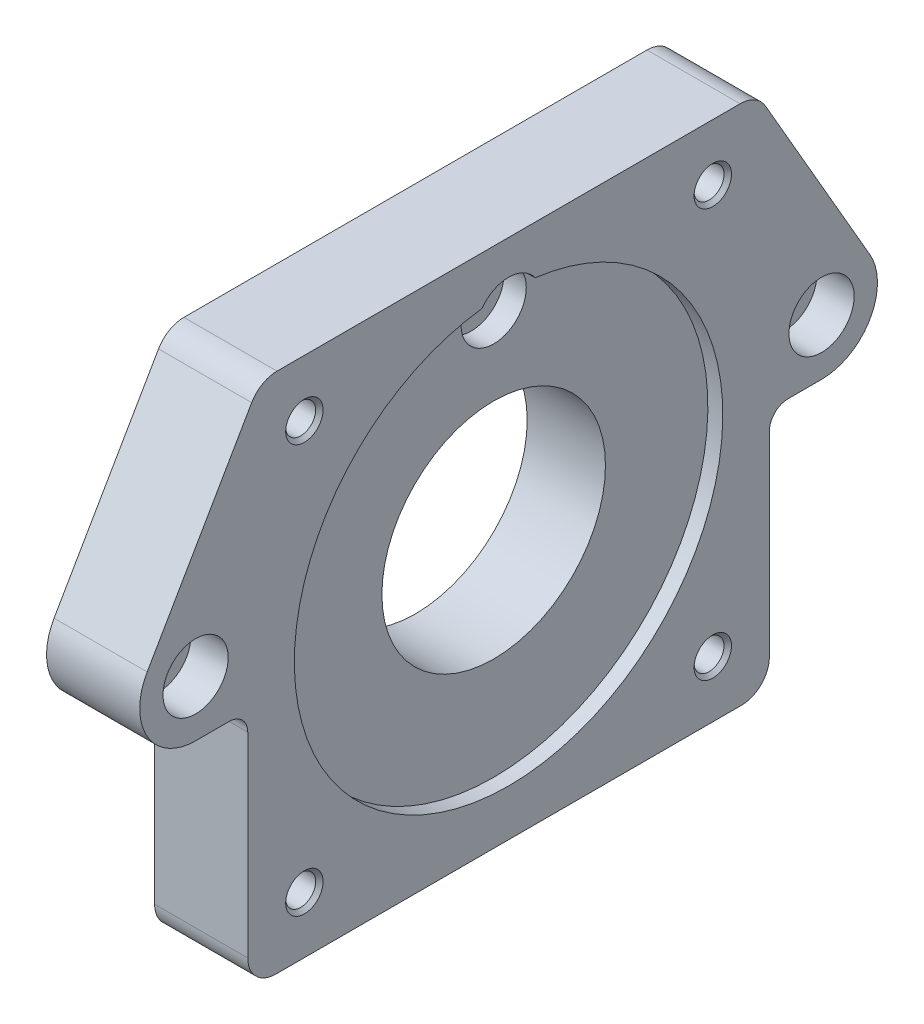
SolidWorks part; units mm, degrees
ref_plane "Front Plane" through (0, 0, 0) normal (0, 0, 1) x (1, 0, 0)
ref_plane "Top Plane" through (0, 0, 0) normal (0, 1, 0) x (1, 0, 0)
ref_plane "Right Plane" through (0, 0, 0) normal (1, 0, 0) x (0, 0, -1)
sketch "Sketch1" plane through (0, 0, 0) normal (1, 0, 0) x (0, 0, -1)
  line L0 (-39.4612, 44.45) -> (39.4612, 44.45)
  line L1 (-43.7816, 41.9556) -> (-61.5889, 11.1125)
  line L2 (43.7816, 41.9556) -> (61.5889, 11.1125)
  line L3 (53.34, -3.175) -> (44.45, -3.175)
  line L4 (-44.45, -3.175) -> (-44.45, -44.45)
  line L5 (-44.45, -44.45) -> (44.45, -44.45)
  line L6 (-53.34, -3.175) -> (-44.45, -3.175)
  line L7 (44.45, -44.45) -> (44.45, -3.175)
  line L9 (-34.798, 34.798) -> (34.798, 34.798) construction
  line L10 (-34.798, 34.798) -> (-34.798, -34.798) construction
  line L11 (-34.798, -34.798) -> (34.798, -34.798) construction
  line L12 (34.798, 34.798) -> (34.798, -34.798) construction
  line L13 (-34.798, 34.798) -> (34.798, -34.798) construction
  line L14 (-34.798, -34.798) -> (34.798, 34.798) construction
  circle A0 centre (0, 0) radius 19.05
  arc A1 (61.5889, 11.1125) -> (53.34, -3.175) centre (53.34, 6.35) cw
  arc A2 (39.4612, 44.45) -> (43.7816, 41.9556) centre (39.4612, 39.4612) cw
  arc A3 (-39.4612, 44.45) -> (-43.7816, 41.9556) centre (-39.4612, 39.4612) ccw
  arc A4 (-53.34, -3.175) -> (-61.5889, 11.1125) centre (-53.34, 6.35) cw
  point P9 (0, 44.45)
  point P12 (0, -44.45)
  point P15 (69.8378, -3.175)
  point P18 (42.3415, 44.45)
  point P21 (-42.3415, 44.45)
  point P24 (-69.8378, -3.175)
  dimension "D1" = 38.1
  dimension "D2" = 88.9
  dimension "D6" = 69.596
  dimension "D7" = 88.9
  dimension "D8" = 9.525
  dimension "D10" = 106.68
  dimension "D3" = 47.625
  dimension "D4" = 60
  dimension "D5" = 44.45
extrude "Boss-Extrude1" add sketch "Sketch1" along normal blind 15.875
fillet "Fillet2" radius 3.175 2 edges at (7.9375, -3.175, -44.45) (7.9375, -3.175, 44.45)
fillet "Fillet3" radius 4.7752 2 edges at (7.9375, -44.45, -44.45) (7.9375, -44.45, 44.45)
sketch "Sketch6" plane through (15.875, 0, 0) normal (1, 0, 0) x (0, 0, -1)
  circle A0 centre (0, 0) radius 36.51
  dimension "D1" = 73.02
extrude "Cut-Extrude2" cut sketch "Sketch6" against normal blind 2.54
hole_wizard "CBORE for 1/4 Socket Head Cap Screw1" positions "Sketch4" profile "Sketch3" counterbore size "1/4" standard "ANSI Inch" end condition through all
sketch "Sketch4" plane through (15.875, 0, 0) normal (1, 0, 0) x (0, 0, -1)
  line L1 (39.4612, 44.45) -> (-39.4612, 44.45) construction
  point P0 (-53.34, 6.35)
  point P14 (53.34, 6.35)
  point P35 (0, 33.02)
  dimension "D1" = 11.43
sketch "Sketch3" plane through (15.875, 6.35, 53.34) normal (0, 1, 0) x (0, 0, -1)
  line L0 (0, 0) -> (0, 15.875)
  line L1 (0, 15.875) -> (3.2639, 15.875)
  line L3 (3.2639, 15.875) -> (3.2639, 6.35)
  line L4 (3.2639, 6.35) -> (5.5562, 6.35)
  line L5 (5.5562, 6.35) -> (5.5562, 0)
  line L7 (5.5562, 0) -> (0, 0)
  line L11 (0, -6.35) -> (0, 107.95) construction
  dimension "Thru Hole Dia." = 6.5278
  dimension "Thru Hole Depth" = 15.875
  dimension "C'Bore Dia." = 11.1125
  dimension "C'Bore Depth" = 6.35
hole_wizard "1/4-20 Tapped Hole1" positions "Sketch7" profile "Sketch8" tap size "1/4-20" standard "ANSI Inch"
sketch "Sketch7" plane through (15.875, 0, 0) normal (1, 0, 0) x (0, 0, -1)
  line L1 (-34.8, 34.8) -> (34.8, 34.8) construction
  line L2 (-34.8, 34.8) -> (-34.8, -34.8) construction
  line L3 (-34.8, -34.8) -> (34.8, -34.8) construction
  line L4 (34.8, 34.8) -> (34.8, -34.8) construction
  line L5 (-34.8, 34.8) -> (34.8, -34.8) construction
  line L6 (-34.8, -34.8) -> (34.8, 34.8) construction
  point P2 (34.8, -34.8)
  point P47 (-34.8, 34.8)
  point P48 (-34.8, -34.8)
  point P49 (34.8, 34.8)
  point P54 (0, 0)
  dimension "D1" = 69.6
  dimension "D2" = 69.6
sketch "Sketch8" plane through (15.875, -34.8, -34.8) normal (0, 1, 0) x (0, 0, -1)
  line L0 (0, 0) -> (0, 20.5838)
  line L1 (0, 20.5838) -> (2.5527, 19.05)
  line L2 (2.5527, 19.05) -> (2.5527, 0.635)
  line L3 (2.5527, 0.635) -> (3.1877, 0)
  line L5 (3.1877, 0) -> (0, 0)
  line L6 (-2.5527, 0.635) -> (-3.1877, 0) construction
  line L10 (0, 20.5838) -> (-2.5527, 19.05) construction
  line L11 (0, -6.35) -> (0, 107.95) construction
  dimension "Tap Drill Dia." = 5.1054
  dimension "Tap Drill Depth" = 19.05
  dimension "Near C'Sink Dia." = 6.3754
  dimension "Near C'Sink Angle" = 90
  dimension "Drill Angle" = 118
cosmetic thread "Hole Thread1" parameters "D1"=15.24, "D2"=6.35
cosmetic thread "Hole Thread2" parameters "D1"=15.24, "D2"=6.35
cosmetic thread "Hole Thread3" parameters "D1"=15.24, "D2"=6.35
cosmetic thread "Hole Thread4" parameters "D1"=15.24, "D2"=6.35
chamfer "Chamfer1" [suppressed] distance 0.508 angle 45
